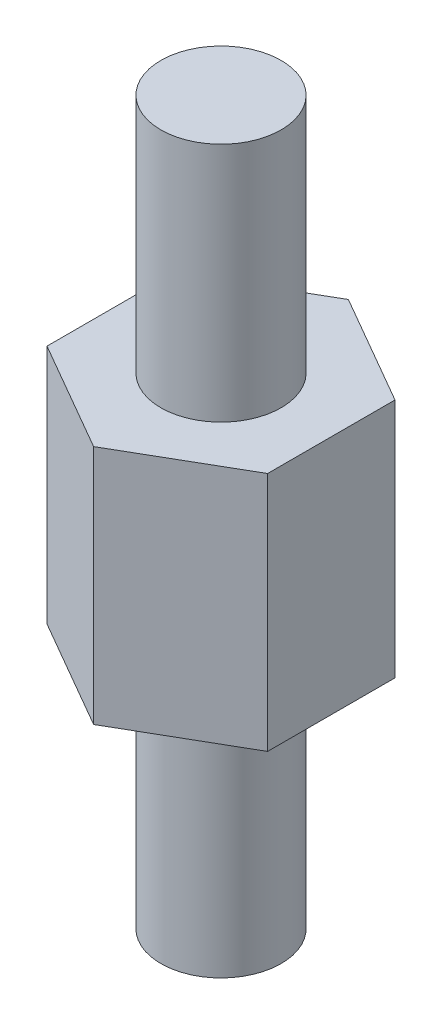
SolidWorks part; units mm, degrees
ref_plane "Спереди" through (0, 0, 0) normal (0, 0, 1) x (1, 0, 0)
ref_plane "Сверху" through (0, 0, 0) normal (0, 1, 0) x (1, 0, 0)
ref_plane "Справа" through (0, 0, 0) normal (1, 0, 0) x (0, 0, -1)
sketch "Эскиз1" plane through (0, 0, 0) normal (0, 1, 0) x (1, 0, 0)
  line L1 (0, -3.1754) -> (2.75, -1.5877)
  line L2 (2.75, -1.5877) -> (2.75, 1.5877)
  line L3 (2.75, 1.5877) -> (0, 3.1754)
  line L4 (0, 3.1754) -> (-2.75, 1.5877)
  line L5 (-2.75, 1.5877) -> (-2.75, -1.5877)
  line L6 (-2.75, -1.5877) -> (0, -3.1754)
  circle A0 centre (0, 0) radius 2.75 construction
  dimension "D1" = 5.5
extrude "Бобышка-Вытянуть1" add sketch "Эскиз1" along normal blind 6
sketch "Эскиз2" plane through (0, 6, 0) normal (0, 1, 0) x (1, 0, 0)
  circle A0 centre (0, 0) radius 1.5
  dimension "D1" = 3
extrude "Бобышка-Вытянуть4" add sketch "Эскиз2" along normal blind 6 separate body
sketch "Эскиз3" plane through (0, 0, 0) normal (0, -1, 0) x (1, 0, 0)
  circle A0 centre (0, 0) radius 1.5
  circle A1 centre (0, 0) radius 1.5 construction
extrude "Бобышка-Вытянуть5" add sketch "Эскиз3" along normal blind 6
